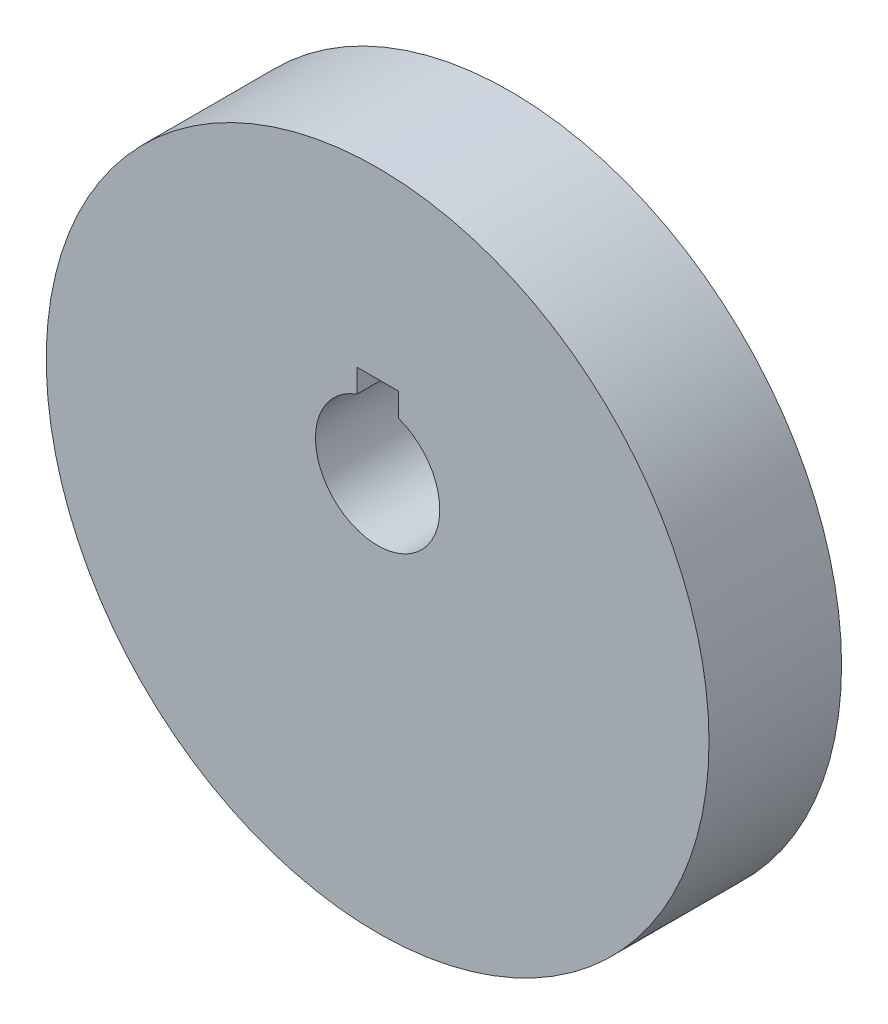
SolidWorks part; units mm, degrees
material "Brass"
ref_plane "Front Plane" through (0, 0, 0) normal (0, 0, 1) x (1, 0, 0)
ref_plane "Top Plane" through (0, 0, 0) normal (0, 1, 0) x (1, 0, 0)
ref_plane "Right Plane" through (0, 0, 0) normal (1, 0, 0) x (0, 0, -1)
sketch "Sketch1" plane through (0, 0, 0) normal (0, 0, 1) x (1, 0, 0)
  circle A0 centre (0, -5.08) radius 25.4
  dimension "D1" = 50.8
extrude "Boss-Extrude1" add sketch "Sketch1" along normal blind 10.16
sketch "Sketch2" plane through (0, 0, 0) normal (0, 0, 1) x (1, 0, 0)
  circle A0 centre (0, 0) radius 4.7625
  dimension "D1" = 9.525
extrude "Cut-Extrude2" cut sketch "Sketch2" against normal blind 12.16 and the other way blind 12.16
sketch "Sketch3" plane through (0, 0, 0) normal (0, 0, 1) x (1, 0, 0)
  line L0 (-1.5875, 2.3812) -> (1.5875, 2.3812)
  line L1 (1.5875, 2.3812) -> (1.5875, 6.2865)
  line L2 (1.5875, 6.2865) -> (-1.5875, 6.2865)
  line L3 (-1.5875, 6.2865) -> (-1.5875, 2.3812)
  dimension "D1" = 3.175
  dimension "D2" = 3.9052
extrude "Cut-Extrude4" cut sketch "Sketch3" against normal blind 12.16 and the other way blind 12.16
